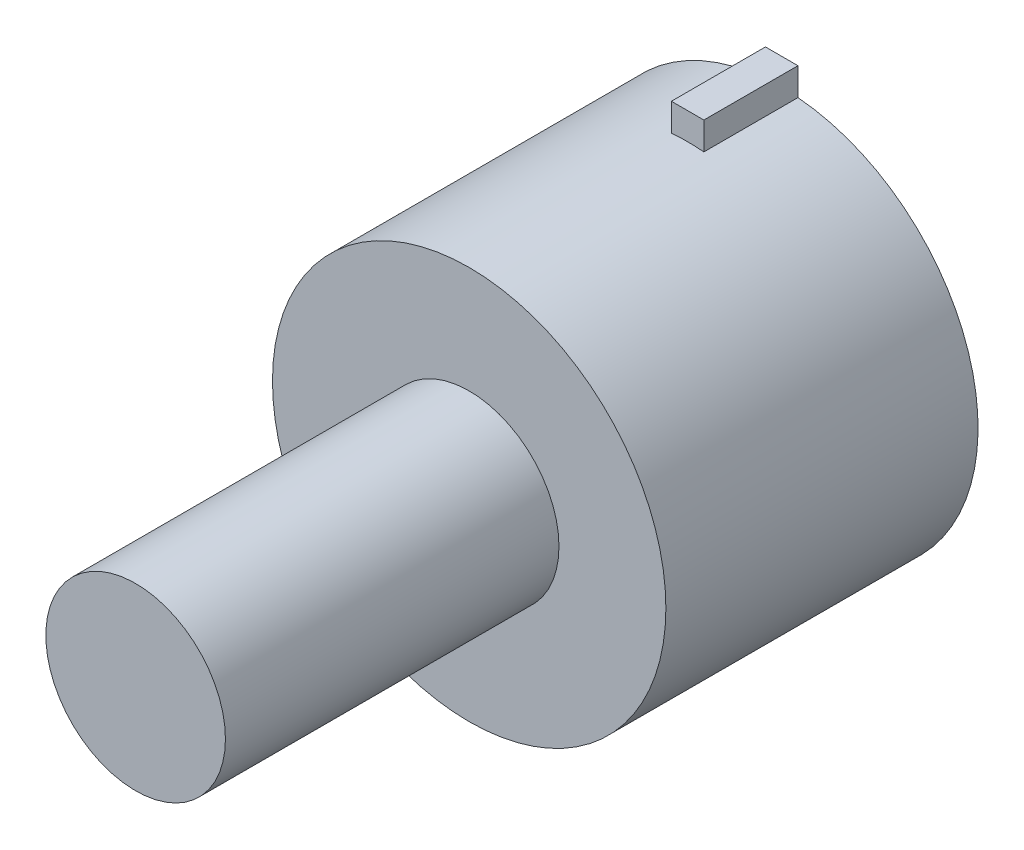
SolidWorks part; units mm, degrees
ref_plane "Front Plane" through (0, 0, 0) normal (0, 0, 1) x (1, 0, 0)
ref_plane "Top Plane" through (0, 0, 0) normal (0, 1, 0) x (1, 0, 0)
ref_plane "Right Plane" through (0, 0, 0) normal (1, 0, 0) x (0, 0, -1)
sketch "Sketch1" plane through (0, 0, 0) normal (0, 0, 1) x (1, 0, 0)
  circle A0 centre (0, 0) radius 4.6
  dimension "D1" = 9.2
extrude "Boss-Extrude1" add sketch "Sketch1" along normal blind 7.3
sketch "Sketch2" plane through (0, 0, 7.3) normal (0, 0, 1) x (1, 0, 0)
  circle A0 centre (0, 0) radius 2.1
  dimension "D1" = 4.2
extrude "Boss-Extrude2" add sketch "Sketch2" along normal blind 7.8
sketch "Sketch3" plane through (0, 0, 7.3) normal (0, 0, 1) x (1, 0, 0)
  line L1 (-0.3715, 4.53) -> (0.3885, 4.53)
  line L2 (-0.3715, 4.53) -> (-0.3715, 5.23)
  line L3 (-0.3715, 5.23) -> (0.3885, 5.23)
  line L4 (0.3885, 4.53) -> (0.3885, 5.23)
  circle A0 centre (0, 0) radius 4.6 construction
  dimension "D1" = 0.76
  dimension "D2" = 0.7
  dimension "D3" = 4.53
extrude "Boss-Extrude3" add sketch "Sketch3" along normal blind 2.2 from offset 7.3
